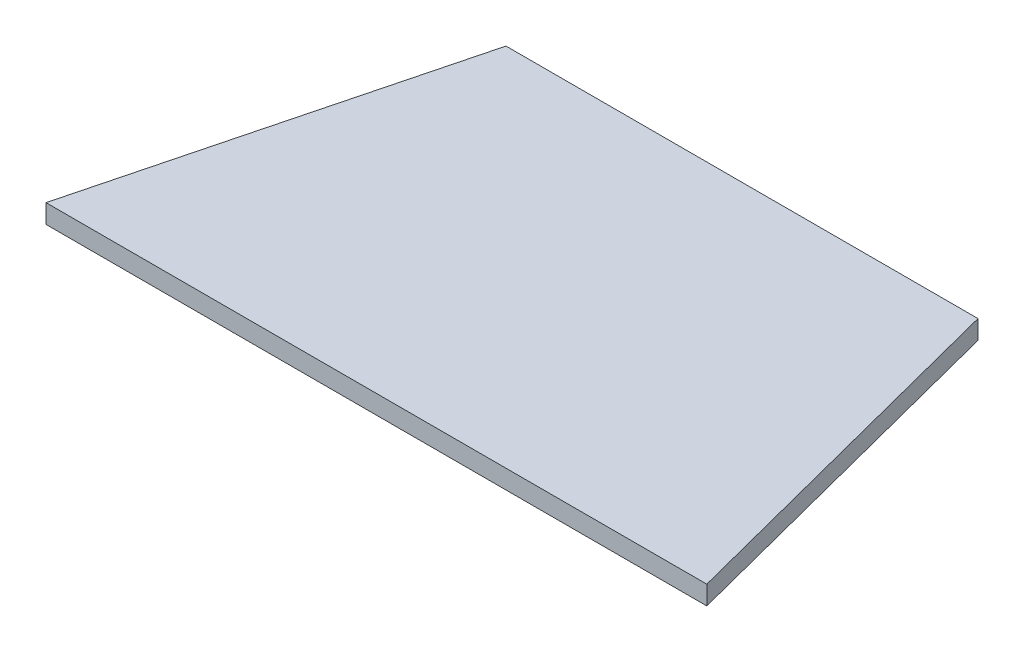
SolidWorks part; units mm, degrees
ref_plane "Płaszczyzna przednia" through (0, 0, 0) normal (0, 0, 1) x (1, 0, 0)
ref_plane "Płaszczyzna górna" through (0, 0, 0) normal (0, 1, 0) x (1, 0, 0)
ref_plane "Płaszczyzna prawa" through (0, 0, 0) normal (1, 0, 0) x (0, 0, -1)
sketch "Szkic1" plane through (0, 0, 0) normal (0, 1, 0) x (1, 0, 0)
  line L0 (-125, 96.8246) -> (-175, -96.8246)
  line L1 (-175, -96.8246) -> (175, -96.8246)
  line L2 (175, -96.8246) -> (125, 96.8246)
  line L3 (125, 96.8246) -> (-125, 96.8246)
  point P2 (0, 96.8246)
  point P5 (0, -96.8246)
  point P7 (-150, 0)
  point P8 (150, 0)
  dimension "D1" = 250
  dimension "D2" = 350
  dimension "D3" = 200
  dimension "D4" = 200
extrude "Dodanie-wyciągnięcie1" add sketch "Szkic1" along normal blind 10
